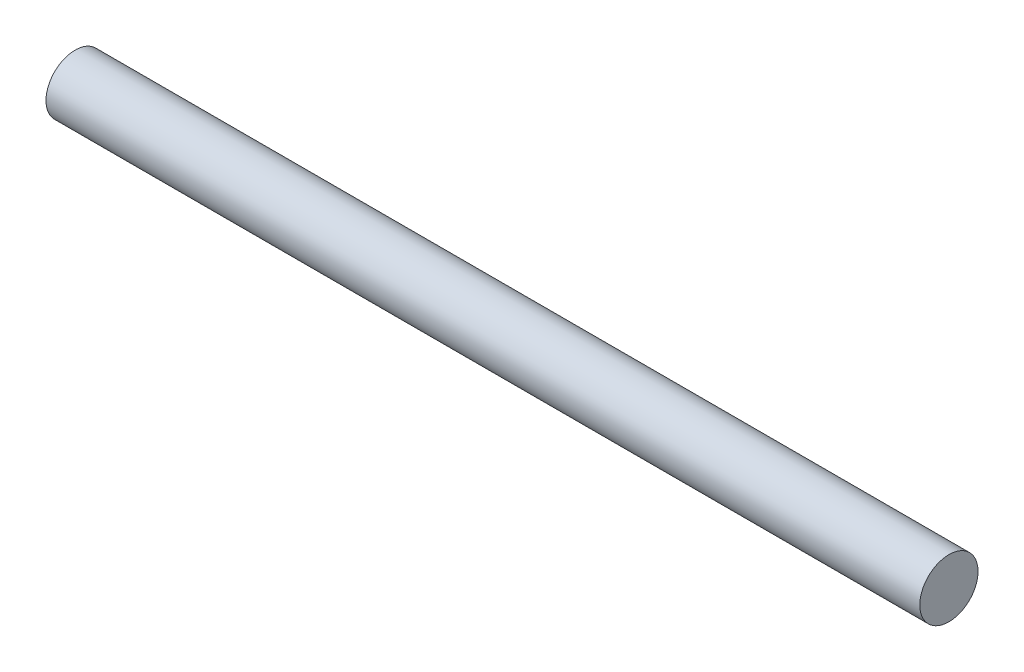
SolidWorks part; units mm, degrees
ref_plane "Front Plane" through (0, 0, 0) normal (0, 0, 1) x (1, 0, 0)
ref_plane "Top Plane" through (0, 0, 0) normal (0, 1, 0) x (1, 0, 0)
ref_plane "Right Plane" through (0, 0, 0) normal (1, 0, 0) x (0, 0, -1)
sketch "Sketch1" plane through (0, 0, 0) normal (1, 0, 0) x (0, 0, -1)
  circle A0 centre (0, 0) radius 6
  dimension "D1" = 12
extrude "Boss-Extrude1" add sketch "Sketch1" along normal blind 180 contours A0
equation "\"WheelDiameter\" = 150mm"
equation "\"WheelRadius\" = \"WheelDiameter\" / 2"
equation "\"DT_WheelWidth\" = 45mm"
equation "\"DT_Wheelbase\" = 300mm"
equation "\"DT_ShaftDiameter\" = 12mm"
equation "\"DT_FrontShaftLength\" = 180mm"
equation "\"DT_RearShaftLength\" = 200mm"
equation "\"DT_BearingWidth\" = 20mm"
equation "\"DT_BearingHousingWidth\" = 60mm"
equation "\"DT_BearingHousingHeight\" = 35mm"
equation "\"DT_ChainPitch\" = 9.525mm"
equation "\"DT_SprocketTeeth\" = 18"
equation "\"DT_SprocketPitchDiameter\" = 54.851mm"
equation "\"DT_SprocketOuterDiameter\" = 60mm"
equation "\"DT_SprocketThickness\" = 6mm"
equation "\"DT_SprocketHubDiameter\" = 25mm"
equation "\"DT_SprocketHubLength\" = 20mm"
equation "\"DT_CouplingDiameter\" = 30mm"
equation "\"DT_CouplingLength\" = 35mm"
equation "\"DT_MotorDiameter\" = 60mm"
equation "\"DT_MotorLength\" = 120mm"
equation "\"DT_MotorShaftDiameter\" = 8mm"
equation "\"DT_MotorShaftLength\" = 20mm"
